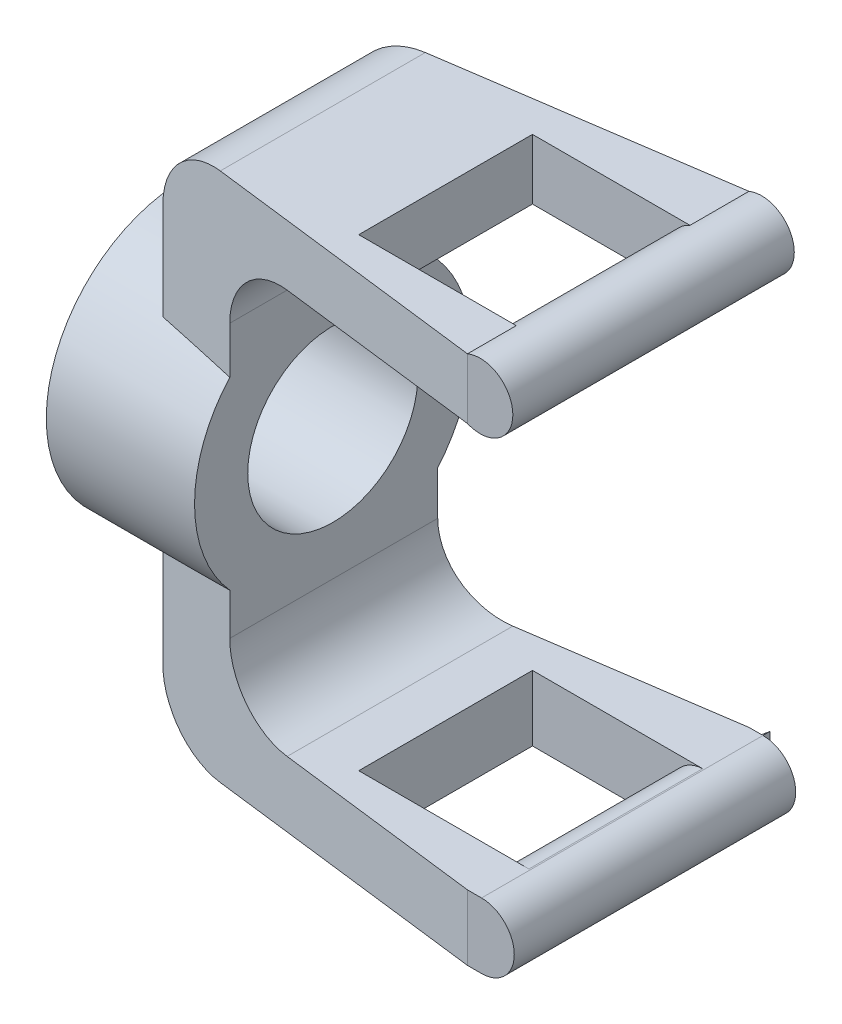
SolidWorks part; units mm, degrees
ref_plane "Front Plane" through (0, 0, 0) normal (0, 0, 1) x (1, 0, 0)
ref_plane "Top Plane" through (0, 0, 0) normal (0, 1, 0) x (1, 0, 0)
ref_plane "Right Plane" through (0, 0, 0) normal (1, 0, 0) x (0, 0, -1)
sketch "Sketch2" plane through (0, 0, 0) normal (0, 0, 1) x (1, 0, 0)
  line L0 (-14.1044, 47.7793) -> (-57.4638, 47.7793)
  line L1 (-57.4638, 47.7793) -> (-57.4638, -13.9196)
  line L2 (-57.4638, -13.9196) -> (-13.8871, -13.9196)
  line L3 (-13.8871, -13.9196) -> (-13.8871, -23.9196)
  line L4 (-14.1044, 47.7793) -> (-14.1044, 57.0035)
  line L5 (-14.1044, 57.0035) -> (-69.1159, 57.0035)
  line L6 (-69.1159, 57.0035) -> (-69.1159, -23.9196)
  line L7 (-69.1159, -23.9196) -> (-13.8871, -23.9196)
extrude "Boss-Extrude1" add sketch "Sketch2" along normal blind 60
sketch "Sketch3" plane through (-14.1044, 0, 0) normal (1, 0, 0) x (0, 0, -1)
  line L0 (-30, 47.7793) -> (-30, -13.9196)
  line L1 (-60, 47.7793) -> (0, 47.7793) construction
  line L2 (-60, -13.9196) -> (0, -13.9196) construction
  line L3 (-60, 57.0035) -> (0, 57.0035) construction
  line L5 (-43.2717, -23.1439) -> (-43.2717, 57.0035)
  line L6 (-43.2717, 57.0035) -> (-16.7283, 57.0035)
  line L7 (-16.7283, -23.1439) -> (-16.7283, 57.0035)
  line L8 (-43.2717, -23.1439) -> (-16.7283, 57.0035) construction
  line L9 (-43.2717, 57.0035) -> (-16.7283, -23.1439) construction
  line L10 (-43.2717, -23.1439) -> (-43.2717, -35.2235)
  line L11 (-43.2717, -35.2235) -> (-16.7283, -35.2235)
  line L12 (-16.7283, -35.2235) -> (-16.7283, -23.1439)
  point P6 (-30, 16.9298)
extrude "Cut-Extrude1" cut sketch "Sketch3" against normal blind 26
sketch "Sketch4" plane through (0, 0, 16.7283) normal (0, 0, 1) x (1, 0, 0)
  line L0 (-14.1044, 47.7793) -> (-14.1044, 57.0035) construction
  line L1 (-13.8871, -23.9196) -> (-13.8871, -13.9196) construction
  circle A0 centre (-14.1044, 52.3914) radius 5
  circle A1 centre (-13.8871, -18.9196) radius 5
extrude "Boss-Extrude2" add sketch "Sketch4" along normal blind 34 and the other way blind 9
sketch "Sketch5" plane through (0, 57.0035, 0) normal (0, 1, 0) x (1, 0, 0)
  line L0 (-14.1044, -7.7283) -> (-16.0352, -7.7283)
  line L1 (-16.0352, -7.7283) -> (-69.1159, -15.5607)
  line L2 (-69.1159, -60) -> (-69.1159, 0) construction
  line L3 (-69.1159, -15.5607) -> (-69.1159, 0)
  line L4 (-69.1159, 0) -> (-12.5698, 0)
  line L5 (-12.5698, 0) -> (-14.1044, -7.7283)
  line L6 (-69.1159, -44.1797) -> (-16.0352, -50.7283)
  line L7 (-16.0352, -50.7283) -> (-13.8871, -50.7283)
  line L8 (-13.8871, -50.7283) -> (-13.8871, -60)
  line L9 (-13.8871, -60) -> (-69.1159, -60)
  line L10 (-69.1159, -60) -> (-69.1159, -44.1797)
extrude "Cut-Extrude2" cut sketch "Sketch5" against normal blind 117
sketch "Sketch6" plane through (-69.1159, 0, 0) normal (-1, 0, 0) x (0, 0, 1)
  line L0 (15.5607, 16.5419) -> (44.1797, 16.5419)
  line L1 (15.5607, -23.9196) -> (15.5607, 57.0035) construction
  line L2 (44.1797, -23.9196) -> (44.1797, 57.0035) construction
  circle A0 centre (29.8702, 16.5419) radius 13
extrude "Cut-Extrude3" cut sketch "Sketch6" against normal blind 31 contours L0 A0 | L0 A0
sketch "Sketch7" plane through (-69.1159, 0, 0) normal (-1, 0, 0) x (0, 0, 1)
  circle A0 centre (29.8702, 16.5419) radius 13
  circle A1 centre (29.8702, 16.5419) radius 21.1242
extrude "Boss-Extrude3" add sketch "Sketch7" along normal blind 11 and the other way up to vertex
fillet "Fillet1" radius 10 4 edges at (-69.1159, -23.9196, 29.8702) (-57.4638, -13.9196, 29.7293) (-57.4638, 47.7793, 29.7293) (-69.1159, 57.0035, 29.8702)
